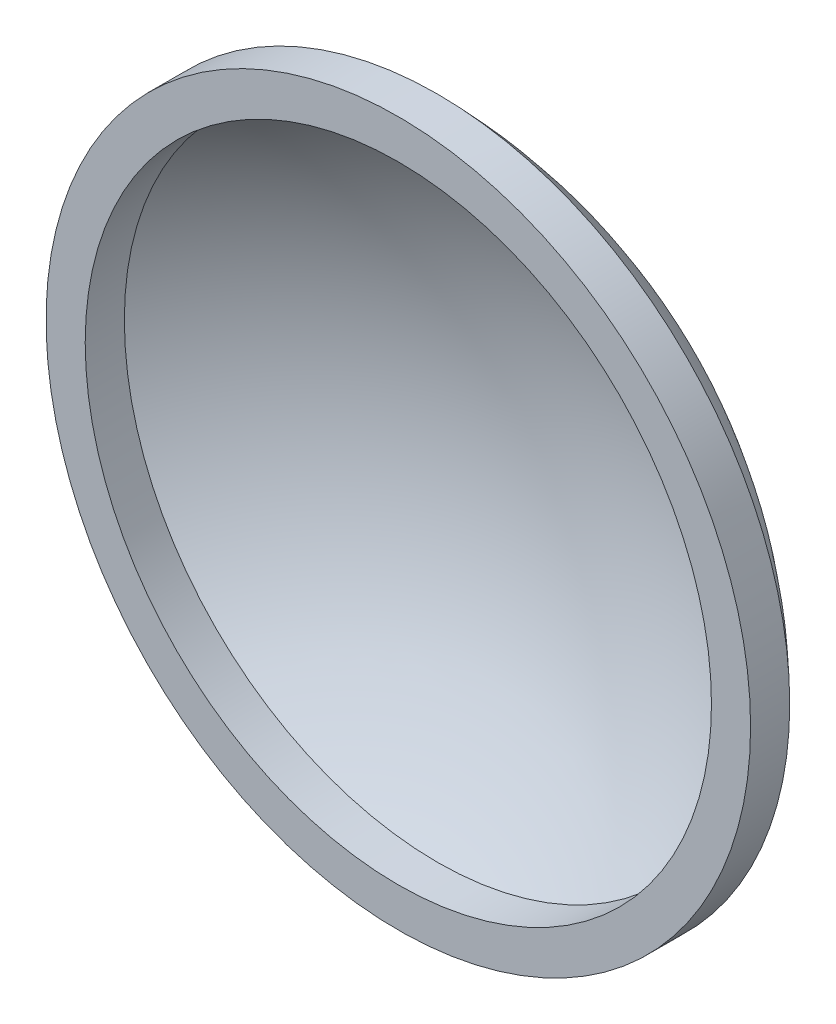
SolidWorks part; units mm, degrees
ref_plane "Front Plane" through (0, 0, 0) normal (0, 0, 1) x (1, 0, 0)
ref_plane "Top Plane" through (0, 0, 0) normal (0, 1, 0) x (1, 0, 0)
ref_plane "Right Plane" through (0, 0, 0) normal (1, 0, 0) x (0, 0, -1)
sketch "Sketch1" plane through (0, 0, 0) normal (1, 0, 0) x (0, 0, -1)
  line L0 (0, 45) -> (0, 40)
  line L1 (5, 40) -> (5, 45) construction
  line L3 (0, 45) -> (5, 45)
  line L7 (0, 40) -> (5, 40)
  line L8 (0, 40) -> (0, 0) construction
  line L9 (20, 0) -> (23.3982, 0)
  line L10 (0, 0) -> (20, 0) construction
  line L11 (5, 40) -> (5, 0) construction
  line L12 (23.3982, 0) -> (23.3982, 45) construction
  line L13 (23.3982, 45) -> (5, 45) construction
  arc A0 (23.3982, 0) -> (5, 45) centre (-40.8333, 0) ccw
  arc A1 (5, 40) -> (20, 0) centre (-40.8333, 0) cw
  dimension "D2" = 15
  dimension "D1" = 5
  dimension "D3" = 40
  dimension "D4" = 5
revolve "Revolve1" add sketch "Sketch1" angle 360 about L10
